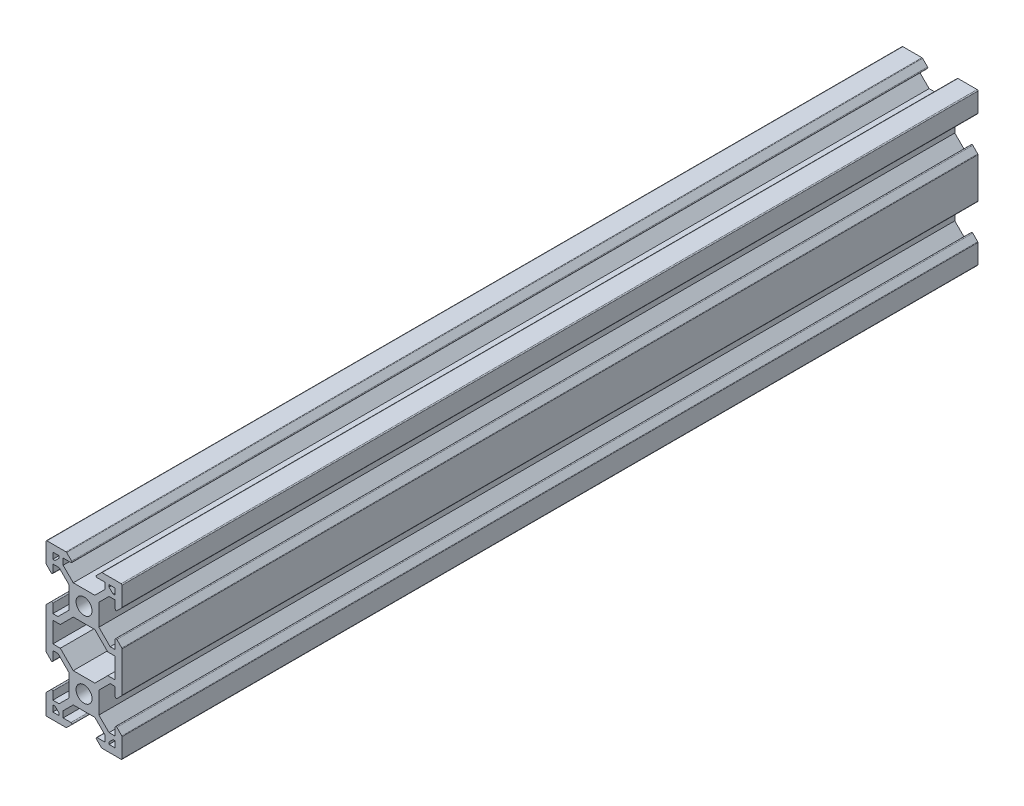
SolidWorks part; units mm, degrees
material "1060 Alloy"
ref_plane "Front Plane" through (0, 0, 0) normal (0, 0, 1) x (1, 0, 0)
ref_plane "Top Plane" through (0, 0, 0) normal (0, 1, 0) x (1, 0, 0)
ref_plane "Right Plane" through (0, 0, 0) normal (1, 0, 0) x (0, 0, -1)
sketch "Sketch1" plane through (0, 0, 0) normal (0, 0, 1) x (1, 0, 0)
  line L0 (8.2, -10) -> (10, -10)
  line L2 (10, -10) -> (10, -4.64)
  line L3 (10, -4.64) -> (8.2, -2.84)
  line L4 (8.2, -2.84) -> (8.2, -5.8007)
  line L5 (8.2, -5.8007) -> (6.8613, -5.8007)
  line L6 (6.8613, -5.8007) -> (3.9007, -2.84)
  line L7 (3.9007, -2.84) -> (3.9007, 2.84)
  line L8 (3.9007, 2.84) -> (6.56, 5.4993)
  line L9 (6.56, 5.4993) -> (8.2, 5.4993)
  line L10 (8.2, 5.4993) -> (8.2, 2.84)
  line L11 (8.2, 2.84) -> (10, 4.64)
  line L12 (10, 4.64) -> (10, 10)
  line L13 (10, 10) -> (4.64, 10)
  line L14 (4.64, 10) -> (2.84, 8.2)
  line L15 (2.84, 8.2) -> (5.4993, 8.2)
  line L16 (5.4993, 8.2) -> (5.4993, 6.56)
  line L17 (5.4993, 6.56) -> (2.84, 3.9007)
  line L18 (2.84, 3.9007) -> (-2.84, 3.9007)
  line L19 (-2.84, 3.9007) -> (-5.4993, 6.56)
  line L20 (-5.4993, 6.56) -> (-5.4993, 8.2)
  line L21 (-5.4993, 8.2) -> (-2.84, 8.2)
  line L22 (-2.84, 8.2) -> (-4.64, 10)
  line L23 (-4.64, 10) -> (-10, 10)
  line L24 (-10, 10) -> (-10, 4.64)
  line L25 (-10, 4.64) -> (-8.2, 2.84)
  line L26 (-8.2, 2.84) -> (-8.2, 5.4993)
  line L27 (-8.2, 5.4993) -> (-6.56, 5.4993)
  line L28 (-6.56, 5.4993) -> (-3.9007, 2.84)
  line L29 (-3.9007, 2.84) -> (-3.9007, -2.84)
  line L30 (-3.9007, -2.84) -> (-6.8613, -5.8007)
  line L31 (-6.8613, -5.8007) -> (-8.2, -5.8007)
  line L32 (-8.2, -5.8007) -> (-8.2, -2.84)
  line L33 (-8.2, -2.84) -> (-10, -4.64)
  line L34 (-10, -4.64) -> (-10, -10)
  line L64 (8.2, -7.3007) -> (8.2, -10)
  line L70 (-8.2, -10) -> (-8.2, -7.3007)
  line L71 (-8.2, -7.3007) -> (-6.24, -7.3007)
  line L72 (-6.24, -7.3007) -> (-2.84, -3.9007)
  line L73 (-2.84, -3.9007) -> (2.84, -3.9007)
  line L74 (2.84, -3.9007) -> (6.24, -7.3007)
  line L75 (6.24, -7.3007) -> (8.2, -7.3007)
  line L76 (-10, -10) -> (-8.2, -10)
  circle A0 centre (0, 0) radius 2.1
  point P46 (0, -3.9007)
  point P47 (0, 3.9007)
  point P49 (-3.9007, 0)
  point P50 (3.9007, 0)
  dimension "D1" = 4.2
  dimension "D8" = 1.8
  dimension "D2" = 20
  dimension "D3" = 20
  dimension "D4" = 5.68
  dimension "D5" = 90
  dimension "D6" = 10
  dimension "D7" = 10
  dimension "D9" = 1.8
  dimension "D10" = 1.8
  dimension "D11" = 1.5
  dimension "D12" = 1.5
  dimension "D13" = 1.64
  dimension "D14" = 1.5
  dimension "D15" = 1.96
extrude "Boss-Extrude2" add sketch "Sketch1" along normal blind 225
sketch "Sketch2" plane through (0, 0, 225) normal (0, 0, 1) x (1, 0, 0)
  line L0 (-8.2, 2.84) -> (-8.2, 5.4993) construction
  line L1 (-5.4993, 8.2) -> (-2.84, 8.2) construction
  line L2 (-8.2, 6.5693) -> (-8.2, 8.2)
  line L3 (-8.2, 8.2) -> (-6.5693, 8.2)
  line L4 (8.2, 5.4993) -> (8.2, 2.84) construction
  line L5 (8.2, 8.2) -> (8.2, 6.5693)
  line L6 (3.9007, 2.84) -> (6.56, 5.4993) construction
  line L7 (-5.4993, 6.56) -> (-5.4993, 8.2) construction
  line L8 (6.56, 5.4993) -> (8.2, 5.4993) construction
  line L11 (6.5693, 8.2) -> (6.5693, 6.56)
  line L12 (6.5693, 8.2) -> (6.5693, 7.63)
  line L16 (6.5693, 8.2) -> (8.2, 8.2)
  line L17 (-8.2, 6.5693) -> (-6.56, 6.5693)
  line L18 (-8.2, 6.5693) -> (-7.63, 6.5693)
  line L19 (-7.63, 6.5693) -> (-6.5693, 7.63)
  line L20 (6.5693, 7.63) -> (7.63, 6.5693)
  line L22 (7.63, 6.5693) -> (8.2, 6.5693)
  line L24 (-6.5693, 7.63) -> (-6.5693, 8.2)
  dimension "D5" = 1.5
  dimension "D1" = 1.07
  dimension "D3" = 1.07
  dimension "D2" = 1.07
  dimension "D4" = 1.07
extrude "Cut-Extrude1" cut sketch "Sketch2" against normal through all
fillet "Fillet1" radius 0.25 14 edges at (8.2, 2.84, 112.5) (-10, 4.64, 112.5) (-4.64, 10, 112.5) (4.64, 10, 112.5) (-10, -4.64, 112.5) (-10, 10, 112.5) (10, -4.64, 112.5) (10, 10, 112.5) (8.2, -2.84, 112.5) (-8.2, -2.84, 112.5) (-8.2, 2.84, 112.5) (10, 4.64, 112.5) (2.84, 8.2, 112.5) (-2.84, 8.2, 112.5)
ref_plane "Plane1" through (0, -10, 0) normal (0, -1, 0) x (-1, 0, 0)
mirror "Mirror1" about plane through (0, -10, 0) normal (0, -1, 0) of "Fillet1", "Boss-Extrude2"
mirror "Mirror2" about plane through (0, -10, 0) normal (0, -1, 0) of "Cut-Extrude1"
